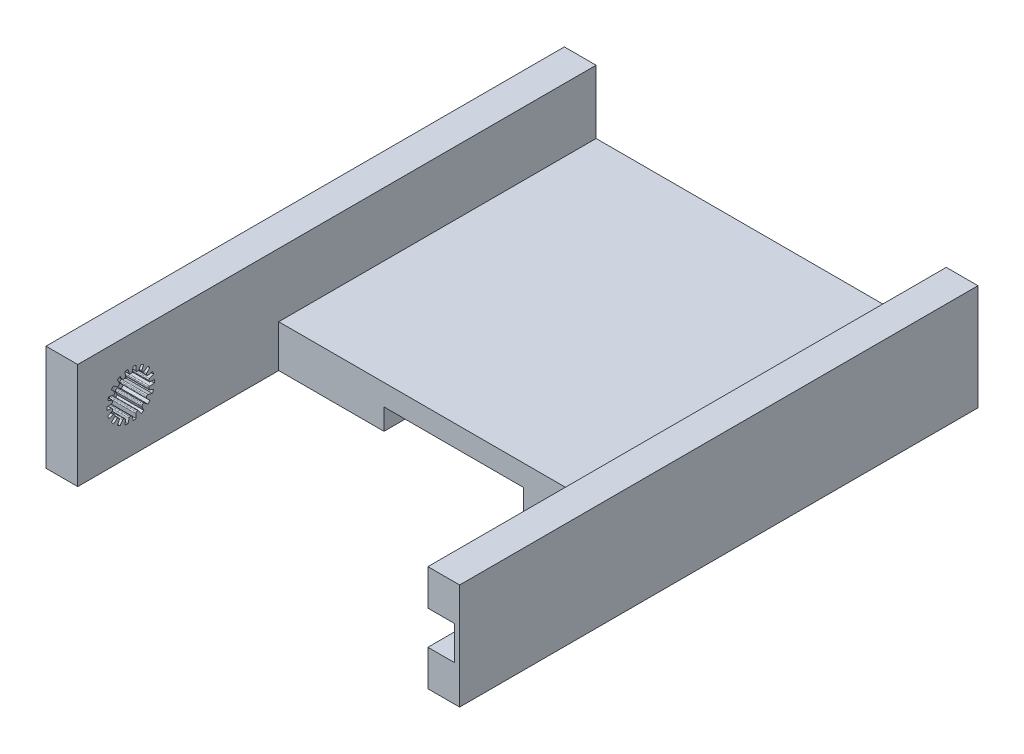
SolidWorks part; units mm, degrees
ref_plane "Front Plane" through (0, 0, 0) normal (0, 0, 1) x (1, 0, 0)
ref_plane "Top Plane" through (0, 0, 0) normal (0, 1, 0) x (1, 0, 0)
ref_plane "Right Plane" through (0, 0, 0) normal (1, 0, 0) x (0, 0, -1)
sketch "Sketch1" plane through (0, 0, 0) normal (0, 1, 0) x (1, 0, 0)
  line L0 (0, -55) -> (0, 55) construction
  line L5 (-19.55, 49) -> (-16.55, 49)
  line L6 (-19.55, 49) -> (-19.55, 0)
  line L7 (-19.55, 0) -> (-16.55, 0)
  line L8 (-16.55, 49) -> (-16.55, 0)
  line L9 (16.55, 49) -> (16.55, 0)
  line L10 (19.55, 0) -> (16.55, 0)
  line L11 (19.55, 49) -> (19.55, 0)
  line L12 (19.55, 49) -> (16.55, 49)
  dimension "D1" = 33.1
  dimension "D2" = 3
  dimension "D3" = 49
extrude "Boss-Extrude1" add sketch "Sketch1" along normal blind 10
sketch "Sketch2" plane through (0, 10, 0) normal (0, 1, 0) x (1, 0, 0)
  line L0 (16.55, 49) -> (16.55, 0) construction
  line L1 (-16.55, 49) -> (16.55, 49)
  line L2 (-16.55, 49) -> (-16.55, 19)
  line L3 (-16.55, 19) -> (16.55, 19)
  line L4 (16.55, 49) -> (16.55, 19)
  dimension "D1" = 30
extrude "Boss-Extrude2" add sketch "Sketch2" along normal blind 4 from surface at -10 starting at face at (18.05, 0, -24.5)
sketch "Sketch3" plane through (0, 10, 0) normal (0, 1, 0) x (1, 0, 0)
  line L0 (-16.55, 49) -> (-19.55, 49) construction
  line L1 (-6.6, 49) -> (6.6, 49)
  line L2 (-6.6, 49) -> (-6.6, 19)
  line L3 (-6.6, 19) -> (6.6, 19)
  line L4 (6.6, 49) -> (6.6, 19)
  line L5 (-16.55, 19) -> (16.55, 19) construction
  point P8 (0, 19)
  dimension "D1" = 13.2
extrude "Cut-Extrude1" cut sketch "Sketch3" along normal blind 2 from surface at -10 starting at face at (0, 0, -17)
sketch "Sketch5" plane through (-19.55, 0, 0) normal (-1, 0, 0) x (0, 0, 1)
  line L36 (-49, 10) -> (0, 10) construction
  line L37 (0, 10) -> (0, 0) construction
  line B0 (-4.75, 7.2361) -> (-4.8548, 6.8247)
  line B1 (-5.1452, 6.8247) -> (-5.25, 7.2361)
  line B2 (-4.5123, 6.7643) -> (-4.4701, 7.1867)
  line B3 (-4.0003, 7.0157) -> (-4.2395, 6.665)
  line B4 (-3.9383, 6.4911) -> (-3.7542, 6.8736)
  line B5 (-3.3712, 6.5522) -> (-3.7159, 6.3045)
  line B6 (-3.4924, 6.0381) -> (-3.1885, 6.3345)
  line B7 (-2.9385, 5.9015) -> (-3.3472, 5.7866)
  line B8 (-3.2283, 5.4598) -> (-2.8413, 5.6345)
  line B9 (-2.7545, 5.1421) -> (-3.1778, 5.1739)
  line B10 (-3.1778, 4.8261) -> (-2.7545, 4.8579)
  line B11 (-2.8413, 4.3655) -> (-3.2283, 4.5402)
  line B12 (-3.3472, 4.2134) -> (-2.9385, 4.0985)
  line B13 (-3.1885, 3.6655) -> (-3.4924, 3.9619)
  line B14 (-3.7159, 3.6955) -> (-3.3712, 3.4478)
  line B15 (-3.7542, 3.1264) -> (-3.9383, 3.5089)
  line B16 (-4.2395, 3.335) -> (-4.0003, 2.9843)
  line B17 (-4.4701, 2.8133) -> (-4.5123, 3.2357)
  line B18 (-4.8548, 3.1753) -> (-4.75, 2.7639)
  line B19 (-5.25, 2.7639) -> (-5.1452, 3.1753)
  line B20 (-5.4877, 3.2357) -> (-5.5299, 2.8133)
  line B21 (-5.9997, 2.9843) -> (-5.7605, 3.335)
  line B22 (-6.0617, 3.5089) -> (-6.2458, 3.1264)
  line B23 (-6.6288, 3.4478) -> (-6.2841, 3.6955)
  line B24 (-6.5076, 3.9619) -> (-6.8115, 3.6655)
  line B25 (-7.0615, 4.0985) -> (-6.6528, 4.2134)
  line B26 (-6.7717, 4.5402) -> (-7.1587, 4.3655)
  line B27 (-7.2455, 4.8579) -> (-6.8222, 4.8261)
  line B28 (-6.8222, 5.1739) -> (-7.2455, 5.1421)
  line B29 (-7.1587, 5.6345) -> (-6.7717, 5.4598)
  line B30 (-6.6528, 5.7866) -> (-7.0615, 5.9015)
  line B31 (-6.8115, 6.3345) -> (-6.5076, 6.0381)
  line B32 (-6.2841, 6.3045) -> (-6.6288, 6.5522)
  line B33 (-6.2458, 6.8736) -> (-6.0617, 6.4911)
  line B34 (-5.7605, 6.665) -> (-5.9997, 7.0157)
  line B35 (-5.5299, 7.1867) -> (-5.4877, 6.7643)
  arc B36 (-5.9997, 7.0157) -> (-6.2458, 6.8736) centre (-5, 5) ccw
  arc B37 (-5.5554, 6.6595) -> (-5.6412, 6.6283) centre (-5, 5) ccw
  arc B38 (-4.9543, 6.7494) -> (-4.8548, 6.8247) centre (-4.9517, 6.8494) ccw
  arc B39 (-5.0457, 6.7494) -> (-5.1452, 6.8247) centre (-5.0483, 6.8494) cw
  arc B40 (-4.4446, 6.6595) -> (-4.5123, 6.7643) centre (-4.4128, 6.7543) cw
  arc B41 (-4.3588, 6.6283) -> (-4.2395, 6.665) centre (-4.3221, 6.7213) ccw
  arc B42 (-3.9105, 6.3695) -> (-3.9383, 6.4911) centre (-3.8482, 6.4477) cw
  arc B43 (-3.8405, 6.3108) -> (-3.7159, 6.3045) centre (-3.7743, 6.3857) ccw
  arc B44 (-3.5078, 5.9142) -> (-3.4924, 6.0381) centre (-3.4225, 5.9665) cw
  arc B45 (-3.4621, 5.8352) -> (-3.3472, 5.7866) centre (-3.3743, 5.8829) ccw
  arc B46 (-3.2851, 5.3487) -> (-3.2283, 5.4598) centre (-3.1871, 5.3687) cw
  arc B47 (-3.2692, 5.2588) -> (-3.1778, 5.1739) centre (-3.1703, 5.2736) ccw
  arc B48 (-3.2692, 4.7412) -> (-3.1778, 4.8261) centre (-3.1703, 4.7264) cw
  arc B49 (-3.2851, 4.6513) -> (-3.2283, 4.5402) centre (-3.1871, 4.6313) ccw
  arc B50 (-3.4621, 4.1648) -> (-3.3472, 4.2134) centre (-3.3743, 4.1171) cw
  arc B51 (-3.5078, 4.0858) -> (-3.4924, 3.9619) centre (-3.4225, 4.0335) ccw
  arc B52 (-3.8405, 3.6892) -> (-3.7159, 3.6955) centre (-3.7743, 3.6143) cw
  arc B53 (-3.9105, 3.6305) -> (-3.9383, 3.5089) centre (-3.8482, 3.5523) ccw
  arc B54 (-4.3588, 3.3717) -> (-4.2395, 3.335) centre (-4.3221, 3.2787) cw
  arc B55 (-4.4446, 3.3405) -> (-4.5123, 3.2357) centre (-4.4128, 3.2457) ccw
  arc B56 (-4.9543, 3.2506) -> (-4.8548, 3.1753) centre (-4.9517, 3.1506) cw
  arc B57 (-5.0457, 3.2506) -> (-5.1452, 3.1753) centre (-5.0483, 3.1506) ccw
  arc B58 (-5.5554, 3.3405) -> (-5.4877, 3.2357) centre (-5.5872, 3.2457) cw
  arc B59 (-5.6412, 3.3717) -> (-5.7605, 3.335) centre (-5.6779, 3.2787) ccw
  arc B60 (-6.0895, 3.6305) -> (-6.0617, 3.5089) centre (-6.1518, 3.5523) cw
  arc B61 (-6.1595, 3.6892) -> (-6.2841, 3.6955) centre (-6.2257, 3.6143) ccw
  arc B62 (-6.4922, 4.0858) -> (-6.5076, 3.9619) centre (-6.5775, 4.0335) cw
  arc B63 (-6.5379, 4.1648) -> (-6.6528, 4.2134) centre (-6.6257, 4.1171) ccw
  arc B64 (-6.7149, 4.6513) -> (-6.7717, 4.5402) centre (-6.8129, 4.6313) cw
  arc B65 (-6.7308, 4.7412) -> (-6.8222, 4.8261) centre (-6.8297, 4.7264) ccw
  arc B66 (-6.7308, 5.2588) -> (-6.8222, 5.1739) centre (-6.8297, 5.2736) cw
  arc B67 (-6.7149, 5.3487) -> (-6.7717, 5.4598) centre (-6.8129, 5.3687) ccw
  arc B68 (-6.5379, 5.8352) -> (-6.6528, 5.7866) centre (-6.6257, 5.8829) cw
  arc B69 (-6.4922, 5.9142) -> (-6.5076, 6.0381) centre (-6.5775, 5.9665) ccw
  arc B70 (-6.1595, 6.3108) -> (-6.2841, 6.3045) centre (-6.2257, 6.3857) cw
  arc B71 (-6.0895, 6.3695) -> (-6.0617, 6.4911) centre (-6.1518, 6.4477) ccw
  arc B72 (-5.6412, 6.6283) -> (-5.7605, 6.665) centre (-5.6779, 6.7213) cw
  arc B73 (-5.5554, 6.6595) -> (-5.4877, 6.7643) centre (-5.5872, 6.7543) ccw
  arc B74 (-4.9543, 6.7494) -> (-5.0457, 6.7494) centre (-5, 5) ccw
  arc B75 (-4.3588, 6.6283) -> (-4.4446, 6.6595) centre (-5, 5) ccw
  arc B76 (-3.8405, 6.3108) -> (-3.9105, 6.3695) centre (-5, 5) ccw
  arc B77 (-3.4621, 5.8352) -> (-3.5078, 5.9142) centre (-5, 5) ccw
  arc B78 (-3.2692, 5.2588) -> (-3.2851, 5.3487) centre (-5, 5) ccw
  arc B79 (-6.0895, 6.3695) -> (-6.1595, 6.3108) centre (-5, 5) ccw
  arc B80 (-6.4922, 5.9142) -> (-6.5379, 5.8352) centre (-5, 5) ccw
  arc B81 (-6.7149, 5.3487) -> (-6.7308, 5.2588) centre (-5, 5) ccw
  arc B82 (-6.7308, 4.7412) -> (-6.7149, 4.6513) centre (-5, 5) ccw
  arc B83 (-6.5379, 4.1648) -> (-6.4922, 4.0858) centre (-5, 5) ccw
  arc B84 (-6.1595, 3.6892) -> (-6.0895, 3.6305) centre (-5, 5) ccw
  arc B85 (-5.6412, 3.3717) -> (-5.5554, 3.3405) centre (-5, 5) ccw
  arc B86 (-5.0457, 3.2506) -> (-4.9543, 3.2506) centre (-5, 5) ccw
  arc B87 (-4.4446, 3.3405) -> (-4.3588, 3.3717) centre (-5, 5) ccw
  arc B88 (-3.9105, 3.6305) -> (-3.8405, 3.6892) centre (-5, 5) ccw
  arc B89 (-3.2851, 4.6513) -> (-3.2692, 4.7412) centre (-5, 5) ccw
  arc B90 (-5.25, 7.2361) -> (-5.5299, 7.1867) centre (-5, 5) ccw
  arc B91 (-4.4701, 7.1867) -> (-4.75, 7.2361) centre (-5, 5) ccw
  arc B92 (-3.7542, 6.8736) -> (-4.0003, 7.0157) centre (-5, 5) ccw
  arc B93 (-3.1885, 6.3345) -> (-3.3712, 6.5522) centre (-5, 5) ccw
  arc B94 (-2.8413, 5.6345) -> (-2.9385, 5.9015) centre (-5, 5) ccw
  arc B95 (-2.7545, 4.8579) -> (-2.7545, 5.1421) centre (-5, 5) ccw
  arc B96 (-2.9385, 4.0985) -> (-2.8413, 4.3655) centre (-5, 5) ccw
  arc B97 (-3.3712, 3.4478) -> (-3.1885, 3.6655) centre (-5, 5) ccw
  arc B98 (-4.0003, 2.9843) -> (-3.7542, 3.1264) centre (-5, 5) ccw
  arc B99 (-4.75, 2.7639) -> (-4.4701, 2.8133) centre (-5, 5) ccw
  arc B100 (-5.5299, 2.8133) -> (-5.25, 2.7639) centre (-5, 5) ccw
  arc B101 (-6.2458, 3.1264) -> (-5.9997, 2.9843) centre (-5, 5) ccw
  arc B102 (-6.8115, 3.6655) -> (-6.6288, 3.4478) centre (-5, 5) ccw
  arc B103 (-7.1587, 4.3655) -> (-7.0615, 4.0985) centre (-5, 5) ccw
  arc B104 (-7.2455, 5.1421) -> (-7.2455, 4.8579) centre (-5, 5) ccw
  arc B105 (-7.0615, 5.9015) -> (-7.1587, 5.6345) centre (-5, 5) ccw
  arc B106 (-6.6288, 6.5522) -> (-6.8115, 6.3345) centre (-5, 5) ccw
  arc B107 (-3.5078, 4.0858) -> (-3.4621, 4.1648) centre (-5, 5) ccw
  dimension "D1" = 5
  dimension "D2" = 5
sketch_block_instance "Block1-1"
sketch_block "Block1" parameters "D1"=0.1, "D2"=0.5
extrude "Cut-Extrude2" cut sketch "Sketch5" along normal blind 2.5 from surface at -3 starting at face at (-16.55, 4.6667, -22.6667)
sketch "Sketch6" plane through (-19.55, 0, 0) normal (-1, 0, 0) x (0, 0, 1)
  line L0 (-49, 10) -> (0, 10) construction
  line L1 (0, 10) -> (0, 0) construction
  circle A0 centre (-5, 5) radius 1.6
  dimension "D3" = 3.2
  dimension "D1" = 5
  dimension "D2" = 5
extrude "Cut-Extrude3" cut sketch "Sketch6" against normal blind 2.5 from surface at -36.1 starting at face at (16.55, 4.6667, -22.6667)
sketch "Sketch9" plane through (0, 10, 0) normal (0, 1, 0) x (1, 0, 0)
  line L1 (16.55, 19) -> (16.55, 0) construction
  line L3 (16.55, 0) -> (19.55, 0) construction
  line L5 (16.55, 5) -> (17.55, 5)
  line L6 (17.55, 5) -> (19.05, 0)
  line L7 (16.55, 5) -> (16.55, 0)
  line L8 (16.55, 0) -> (19.05, 0)
  dimension "D1" = 5
  dimension "D2" = 2.5
  dimension "D3" = 1
extrude "Cut-Extrude4" cut sketch "Sketch9" against normal blind 3.2 from offset 3.4
